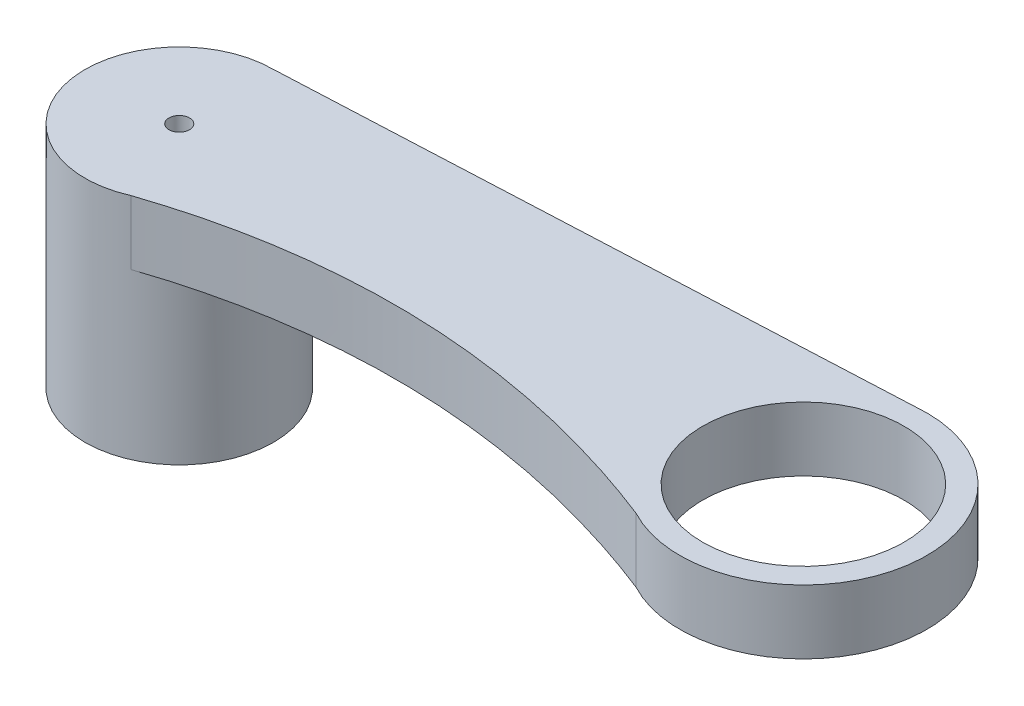
SolidWorks part; units mm, degrees
ref_plane "Płaszczyzna przednia" through (0, 0, 0) normal (0, 0, 1) x (1, 0, 0)
ref_plane "Płaszczyzna górna" through (0, 0, 0) normal (0, 1, 0) x (1, 0, 0)
ref_plane "Płaszczyzna prawa" through (0, 0, 0) normal (1, 0, 0) x (0, 0, -1)
sketch "Szkic1" plane through (0, 0, 0) normal (0, 1, 0) x (1, 0, 0)
  circle A0 centre (0, 0) radius 10.3
  circle A1 centre (0, 0) radius 1.125
  dimension "D1" = 20.6
  dimension "D2" = 2.25
extrude "Dodanie-wyciągnięcie1" add sketch "Szkic1" along normal blind 25 contours A0
hole_wizard "Otwory ustalające Ø2.5mm2" positions "Szkic4" profile "Szkic6" hole size "Ø2.5" standard "Ansi Metric" end condition through all
sketch "Szkic4" plane through (0, 0, 0) normal (0, -1, 0) x (1, 0, 0)
  point P0 (0, 0)
sketch "Szkic6" plane through (0, 0, 0) normal (1, 0, 0) x (0, 0, -1)
  line L0 (0, 0) -> (0, 25)
  line L1 (0, 25) -> (1.125, 25)
  line L2 (1.125, 25) -> (1.125, 0)
  line L5 (1.125, 0) -> (0, 0)
  line L11 (0, -6.35) -> (0, 107.95) construction
  dimension "Średnica otworu na wylot" = 2.25
  dimension "Głębokość otworu na wylot" = 25
sketch "Szkic7" plane through (0, 25, 0) normal (0, 1, 0) x (1, 0, 0)
  line L0 (0, 0) -> (10.1903, 0) construction
  line L1 (10.1903, 0) -> (68.2073, 0) construction
  line L2 (4.1699, -9.4182) -> (22.4618, -3.246) construction
  line L3 (22.4618, -3.246) -> (41.9342, -4.0772) construction
  line L4 (41.9342, -4.0772) -> (61.82, -11.8934) construction
  line L5 (66.9434, 13.4407) -> (0, 10.3)
  arc A0 (61.82, -11.8934) -> (66.9434, 13.4407) centre (68.2073, 0) ccw
  circle A1 centre (0, 0) radius 10.3 construction
  arc A2 (0, 10.3) -> (4.1699, -9.4182) centre (0, 0) cw
  spline S0 degree 3 poles (4.1699, -9.4182) (22.4618, -3.246) (41.9342, -4.0772) (61.82, -11.8934) knots 0 0 0 0 1 1 1 1
  point P15 (61.5163, -11.7252)
  dimension "D1" = 27
extrude "Dodanie-wyciągnięcie3" add sketch "Szkic7" against normal blind 7
hole_wizard "Otwory ustalające Ø2.5mm3" positions "Szkic10" profile "Szkic11" hole size "Ø2.5" standard "Ansi Metric" end condition through all
sketch "Szkic10" plane through (0, 25, 0) normal (0, 1, 0) x (1, 0, 0)
  point P0 (68.2073, 0)
sketch "Szkic11" plane through (68.2073, 25, 0) normal (1, 0, 0) x (0, 0, 1)
  line L0 (0, 0) -> (0, 25)
  line L1 (0, 25) -> (11, 25)
  line L2 (11, 25) -> (11, 0)
  line L5 (11, 0) -> (0, 0)
  line L11 (0, -6.35) -> (0, 107.95) construction
  dimension "Średnica otworu na wylot" = 22
  dimension "Głębokość otworu na wylot" = 25
